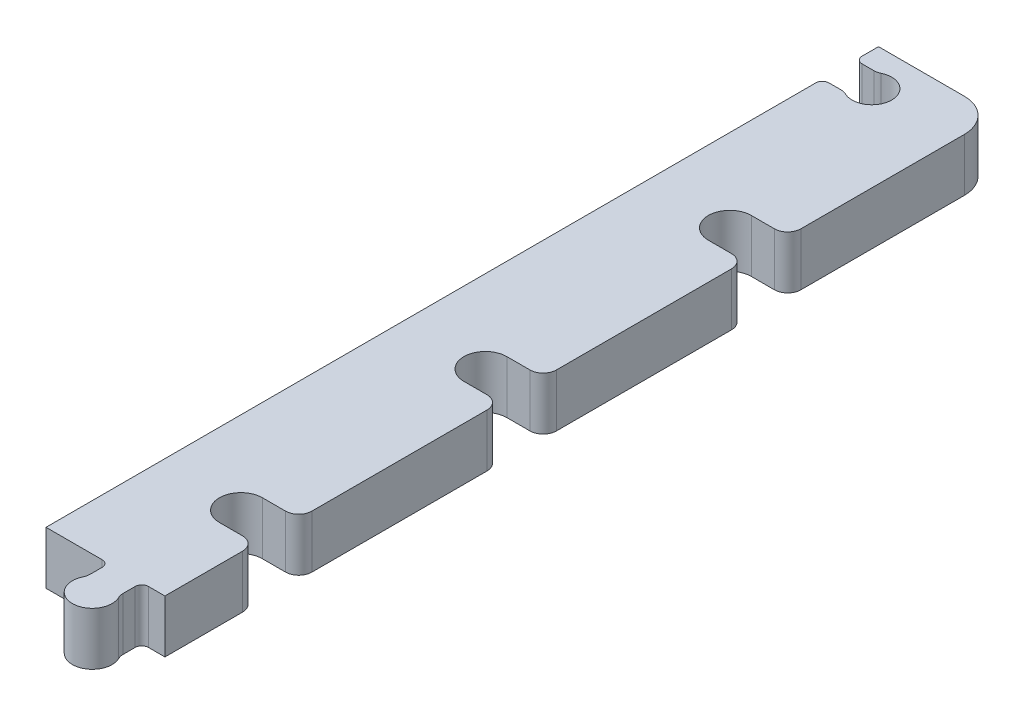
SolidWorks part; units mm, degrees
ref_plane "정면" through (0, 0, 0) normal (0, 0, 1) x (1, 0, 0)
ref_plane "윗면" through (0, 0, 0) normal (0, 1, 0) x (1, 0, 0)
ref_plane "우측면" through (0, 0, 0) normal (1, 0, 0) x (0, 0, -1)
sketch "스케치1" plane through (0, 0, 0) normal (0, 1, 0) x (1, 0, 0)
  line L1 (0, 0) -> (18, 0)
  line L2 (0, 0) -> (0, 126)
  line L3 (0, 126) -> (18, 126)
  line L4 (18, 0) -> (18, 126)
  dimension "D1" = 126
  dimension "D2" = 18
extrude "보스-돌출1" add sketch "스케치1" along normal blind 8
sketch "스케치2" plane through (0, 8, 0) normal (0, 1, 0) x (1, 0, 0)
  line L0 (12.5, 108) -> (12.5, 91) construction
  line L2 (12.5, 91) -> (12.5, 54) construction
  line L3 (12.5, 54) -> (12.5, 17) construction
  line L4 (12.5, 17) -> (12.5, 0) construction
  line L5 (0, 0) -> (18, 0) construction
  line L6 (12.5, 108) -> (12.5, 126) construction
  line L7 (18, 126) -> (0, 126) construction
  line L8 (12.5, 91) -> (18, 91) construction
  line L10 (18, 0) -> (18, 126) construction
  line L12 (12.5, 94.25) -> (18, 94.25)
  line L13 (12.5, 87.75) -> (18, 87.75)
  line L14 (12.5, 54) -> (18, 54) construction
  line L15 (12.5, 57.25) -> (18, 57.25)
  line L16 (12.5, 50.75) -> (18, 50.75)
  line L17 (12.5, 17) -> (18, 17) construction
  line L18 (12.5, 20.25) -> (18, 20.25)
  line L19 (12.5, 13.75) -> (18, 13.75)
  line L20 (0, 126) -> (0, 0) construction
  arc A0 (12.5, 94.25) -> (12.5, 87.75) centre (12.5, 91) ccw
  arc A1 (18, 87.75) -> (18, 94.25) centre (18, 91) ccw
  arc A2 (12.5, 57.25) -> (12.5, 50.75) centre (12.5, 54) ccw
  arc A3 (18, 50.75) -> (18, 57.25) centre (18, 54) ccw
  arc A4 (12.5, 20.25) -> (12.5, 13.75) centre (12.5, 17) ccw
  arc A5 (18, 13.75) -> (18, 20.25) centre (18, 17) ccw
  point P0 (15.25, 91)
  point P18 (15.25, 54)
  point P24 (15.25, 17)
  dimension "D2" = 3.25
  dimension "D1" = 18
  dimension "D3" = 12.5
  dimension "D4" = 17
extrude "컷-돌출1" cut sketch "스케치2" against normal blind 10
fillet "필렛1" radius 5 1 edges at (18, 4, -126)
fillet "필렛2" radius 2 6 edges at (18, 4, -94.25) (18, 4, -87.75) (18, 4, -57.25) (18, 4, -50.75) (18, 4, -13.75) (18, 4, -20.25)
sketch "스케치10" plane through (0, 0, 0) normal (0, -1, 0) x (1, 0, 0)
  line L0 (12, 5) -> (12, 0) construction
  line L1 (14.5, 3.3417) -> (12, 3.3417) construction
  line L2 (9.5, 0) -> (9.5, 2.8206)
  line L3 (9.5, 0) -> (14.5, 0)
  line L4 (14.5, 0) -> (14.5, 2.8206)
  line L5 (12, 3.3417) -> (9.5, 3.3417) construction
  line L6 (9.5, 0) -> (14.5, 3.3417) construction
  line L7 (14.5, 0) -> (9.5, 3.3417) construction
  arc A0 (14.7, 3.6923) -> (9.3, 3.6923) centre (12, 5) ccw
  arc A1 (9.5, 2.8206) -> (9.3, 3.6923) centre (7.5, 2.8206) ccw
  arc A2 (14.5, 2.8206) -> (14.7, 3.6923) centre (16.5, 2.8206) cw
  point P3 (12, 1.6708)
  dimension "D3" = 6
  dimension "D4" = 2
  dimension "D1" = 5
  dimension "D2" = 5
extrude "보스-돌출5" add sketch "스케치10" against normal blind 8
sketch "스케치11" plane through (0, 0, 0) normal (0, -1, 0) x (1, 0, 0)
  line L0 (5, -120) -> (0, -120) construction
  line L1 (3.3417, -122.5) -> (3.3417, -120) construction
  line L2 (0, -117.5) -> (2.8206, -117.5)
  line L3 (0, -117.5) -> (0, -122.5)
  line L4 (0, -122.5) -> (2.8206, -122.5)
  line L5 (3.3417, -120) -> (3.3417, -117.5) construction
  line L6 (0, -117.5) -> (3.3417, -122.5) construction
  line L7 (0, -122.5) -> (3.3417, -117.5) construction
  arc A0 (3.6923, -122.7) -> (3.6923, -117.3) centre (5, -120) ccw
  arc A1 (2.8206, -117.5) -> (3.6923, -117.3) centre (2.8206, -115.5) ccw
  arc A2 (2.8206, -122.5) -> (3.6923, -122.7) centre (2.8206, -124.5) cw
  point P3 (1.6708, -120)
  dimension "D3" = 6
  dimension "D4" = 2
  dimension "D1" = 5
  dimension "D2" = 5
extrude "컷-돌출4" cut sketch "스케치11" against normal blind 8
fillet "필렛3" radius 1 2 edges
fillet "필렛4" radius 1 2 edges at (0, 4, -122.5) (0, 4, -117.5)
